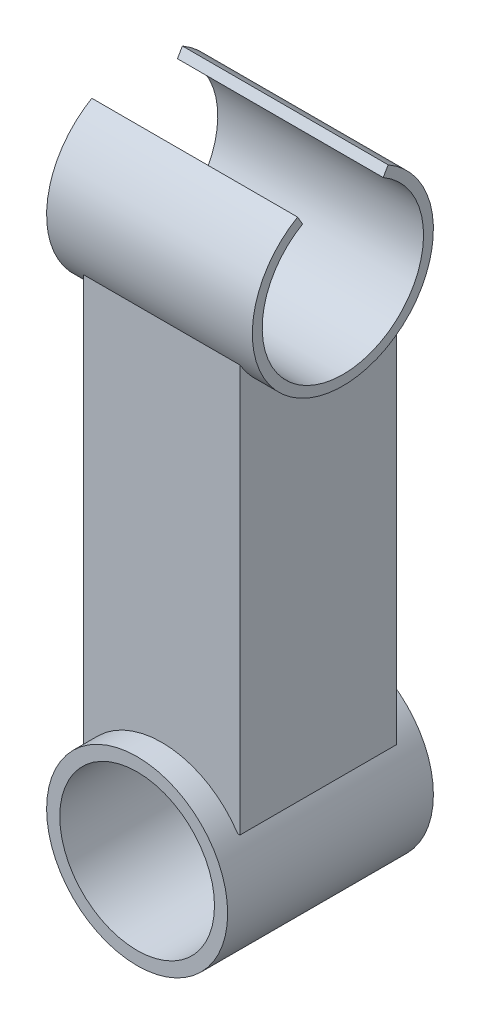
SolidWorks part; units mm, degrees
ref_plane "Front Plane" through (0, 0, 0) normal (0, 0, 1) x (1, 0, 0)
ref_plane "Top Plane" through (0, 0, 0) normal (0, 1, 0) x (1, 0, 0)
ref_plane "Right Plane" through (0, 0, 0) normal (1, 0, 0) x (0, 0, -1)
sketch "Sketch1" plane through (0, 0, 0) normal (1, 0, 0) x (0, 0, -1)
  line L0 (-5.5, 9.5263) -> (-4.9, 8.487)
  line L1 (4.9, 8.487) -> (5.5, 9.5263)
  line L2 (0, 0) -> (0, 11) construction
  line L3 (-4.9, 8.487) -> (0, 0) construction
  line L4 (0, 0) -> (4.9, 8.487) construction
  arc A0 (-4.9, 8.487) -> (4.9, 8.487) centre (0, 0) ccw
  arc A1 (-5.5, 9.5263) -> (5.5, 9.5263) centre (0, 0) ccw
  circle A3 centre (0, 0) radius 11 construction
  circle A4 centre (0, 0) radius 9.8 construction
  point P4 (9.3718, 2.8652)
  point P6 (10.5194, 3.2161)
  dimension "D1" = 22
  dimension "D2" = 1.2
  dimension "D3" = 60
  dimension "D4" = 30
extrude "Boss-Extrude1" add sketch "Sketch1" along normal mid plane 25
sketch "Sketch3" plane through (0, 0, 0) normal (0, 1, 0) x (1, 0, 0)
  line L0 (-7.9, 7.9) -> (7.9, 7.9)
  line L1 (-9.5, -9.5) -> (9.5, -9.5)
  line L2 (-9.5, -9.5) -> (-9.5, 9.5)
  line L3 (-9.5, 9.5) -> (9.5, 9.5)
  line L4 (9.5, -9.5) -> (9.5, 9.5)
  line L5 (-9.5, -9.5) -> (9.5, 9.5) construction
  line L6 (-9.5, 9.5) -> (9.5, -9.5) construction
  line L7 (7.9, -7.9) -> (7.9, 7.9)
  line L8 (-7.9, -7.9) -> (7.9, -7.9)
  line L9 (-7.9, -7.9) -> (-7.9, 7.9)
  point P0 (0, 0)
  dimension "D1" = 19
  dimension "D2" = 1.6
extrude "Boss-Extrude3" add sketch "Sketch3" against normal blind 55
sketch "Sketch2" plane through (0, 0, 0) normal (0, 0, 1) x (1, 0, 0)
  line L0 (0, -61) -> (0, 0) construction
  line L2 (-9.5, -55) -> (9.5, -55) construction
  circle A0 centre (0, -61) radius 11
  circle A1 centre (0, -61) radius 9.4
  point P6 (0, -39.694)
  point P9 (0, -49.9952)
  dimension "D1" = 6
  dimension "D3" = 22
  dimension "D2" = 1.6
extrude "Boss-Extrude2" add sketch "Sketch2" along normal mid plane 25
sketch "Sketch4" plane through (0, 0, 0) normal (1, 0, 0) x (0, 0, -1)
  line L0 (-9.5, 0) -> (9.5, 0) construction
  circle A0 centre (0, 0) radius 9.8
  arc A1 (-4.9, 8.487) -> (4.9, 8.487) centre (0, 0) ccw construction
extrude "Cut-Extrude1" cut sketch "Sketch4" against normal mid plane 40
sketch "Sketch5" plane through (0, 0, 0) normal (0, 0, 1) x (1, 0, 0)
  circle A0 centre (0, -61) radius 9.4
  circle A1 centre (0, -61) radius 9.4 construction
extrude "Cut-Extrude2" cut sketch "Sketch5" against normal mid plane 40
